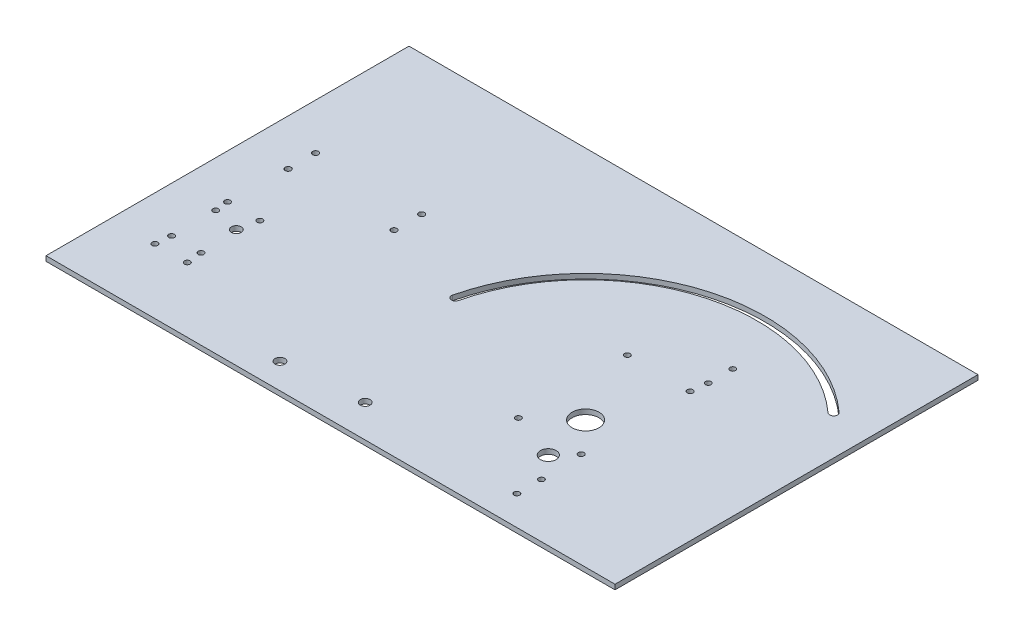
SolidWorks part; units mm, degrees
ref_plane "Front Plane" through (0, 0, 0) normal (0, 0, 1) x (1, 0, 0)
ref_plane "Top Plane" through (0, 0, 0) normal (0, 1, 0) x (1, 0, 0)
ref_plane "Right Plane" through (0, 0, 0) normal (1, 0, 0) x (0, 0, -1)
sketch "Sketch1" plane through (0, 0, 0) normal (0, 1, 0) x (1, 0, 0)
  line L1 (-158.75, 88.9) -> (158.75, 88.9)
  line L2 (-158.75, 88.9) -> (-158.75, -88.9)
  line L3 (-158.75, -88.9) -> (158.75, -88.9)
  line L4 (158.75, 88.9) -> (158.75, -88.9)
  line L5 (-158.75, 88.9) -> (158.75, -88.9) construction
  line L6 (-158.75, -88.9) -> (158.75, 88.9) construction
  circle A0 centre (-111.76, -12.7) radius 3.175
  circle A1 centre (107.95, -6.35) radius 8.7313
  circle A4 centre (-129.032, 55.88) radius 1.905
  circle A5 centre (-60.452, 55.88) radius 1.905
  circle A7 centre (-129.032, 38.1) radius 1.905
  circle A8 centre (-60.452, 38.1) radius 1.905
  point P0 (0, 0)
  dimension "D3" = 6.35
  dimension "D4" = 17.4625
  dimension "D14" = 3.81
  dimension "D17" = 17.78
  dimension "D1" = 317.5
  dimension "D2" = 177.8
  dimension "D5" = 46.99
  dimension "D6" = 266.7
  dimension "D7" = 95.25
  dimension "D8" = 76.2
  dimension "D13" = 29.718
  dimension "D15" = 68.58
  dimension "D16" = 127
extrude "Boss-Extrude1" add sketch "Sketch1" along normal blind 3.175
sketch "Sketch2" plane through (0, 3.175, 0) normal (0, 1, 0) x (1, 0, 0)
  line L0 (-158.75, 88.9) -> (-158.75, -88.9) construction
  line L1 (-158.75, -88.9) -> (158.75, -88.9) construction
  circle A0 centre (-89.0817, -33.177) radius 1.905
  circle A1 centre (-132.1376, -36.4483) radius 1.905
  dimension "D1" = 3.81
  dimension "D2" = 69.6683
  dimension "D3" = 52.4517
  dimension "D4" = 55.723
  dimension "D5" = 43.18
extrude "Cut-Extrude1" [suppressed] cut sketch "Sketch2" against normal through all
sketch "Sketch3" plane through (0, 0, 0) normal (0, -1, 0) x (-1, 0, 0)
  line L0 (158.75, -88.9) -> (-158.75, -88.9) construction
  line L1 (158.75, 88.9) -> (158.75, -88.9) construction
  circle A0 centre (23.8295, -72.39) radius 3.175
  circle A1 centre (-26.7643, -67.818) radius 3.175
  dimension "D1" = 6.35
  dimension "D2" = 4.572
  dimension "D3" = 16.51
  dimension "D4" = 185.5143
  dimension "D5" = 50.8
extrude "Cut-Extrude2" cut sketch "Sketch3" against normal through all
sketch "Sketch4" plane through (0, 3.175, 0) normal (0, 1, 0) x (1, 0, 0)
  line L0 (-158.75, -88.9) -> (158.75, -88.9) construction
  line L1 (158.75, 88.9) -> (133.35, 88.9)
  line L2 (158.75, 88.9) -> (158.75, -88.9)
  line L3 (158.75, -88.9) -> (133.35, -88.9)
  line L4 (133.35, 88.9) -> (133.35, -88.9)
  dimension "D1" = 25.4
extrude "Cut-Extrude3" cut sketch "Sketch4" against normal through all
sketch "Sketch5" plane through (0, 3.175, 0) normal (0, 1, 0) x (1, 0, 0)
  line L0 (133.35, 88.9) -> (-158.75, 88.9) construction
  line L1 (133.35, 88.9) -> (133.35, -88.9) construction
  circle A0 centre (115.57, -38.1) radius 5.08
  dimension "D3" = 10.16
  dimension "D1" = 127
  dimension "D2" = 17.78
extrude "Cut-Extrude4" cut sketch "Sketch5" against normal through all
sketch "Sketch6" plane through (0, 0, 0) normal (0, -1, 0) x (1, 0, 0)
  line L0 (-158.75, 88.9) -> (133.35, 88.9) construction
  line L1 (133.35, -88.9) -> (133.35, 88.9) construction
  line L2 (133.35, -88.9) -> (-158.75, -88.9) construction
  circle A0 centre (127, 69.85) radius 1.8034
  circle A2 centre (127, 53.975) radius 1.8034
  circle A3 centre (127, -53.975) radius 1.8034
  circle A4 centre (127, -69.85) radius 1.8034
  dimension "D4" = 3.6068
  dimension "D5" = 6.35
  dimension "D1" = 15.875
  dimension "D2" = 19.05
  dimension "D3" = 6.35
  dimension "D6" = 15.875
  dimension "D7" = 19.05
extrude "Cut-Extrude5" cut sketch "Sketch6" against normal through all
sketch "Sketch7" plane through (0, 3.175, 0) normal (0, 1, 0) x (1, 0, 0)
  line L0 (133.35, 88.9) -> (133.35, -88.9) construction
  line L1 (133.35, 88.9) -> (-158.75, 88.9) construction
  line L2 (-158.75, 88.9) -> (-158.75, -88.9) construction
  line L3 (-158.75, -88.9) -> (133.35, -88.9) construction
  circle A1 centre (125.73, 43.4975) radius 1.8415
  circle A2 centre (85.09, 43.4975) radius 1.8415
  circle A3 centre (85.09, -26.9875) radius 1.8415
  circle A4 centre (125.73, -26.9875) radius 1.8415
  circle A5 centre (-130.175, -46.99) radius 1.8415
  circle A6 centre (-109.22, -46.99) radius 1.8415
  circle A7 centre (-129.2225, -37.1475) radius 1.8415
  circle A8 centre (-110.1725, -37.1475) radius 1.8415
  circle A9 centre (-129.2225, -8.5725) radius 1.8415
  circle A10 centre (-130.175, 0) radius 1.8415
  circle A11 centre (-109.22, 0) radius 1.8415
  dimension "D1" = 7.62
  dimension "D5" = 3.683
  dimension "D10" = 3.683
  dimension "D15" = 3.683
  dimension "D2" = 40.64
  dimension "D3" = 70.485
  dimension "D4" = 61.9125
  dimension "D6" = 28.575
  dimension "D7" = 20.955
  dimension "D8" = 0.9525
  dimension "D9" = 19.05
  dimension "D11" = 88.9
  dimension "D12" = 8.5725
  dimension "D13" = 28.575
  dimension "D14" = 9.8425
extrude "Cut-Extrude6" cut sketch "Sketch7" against normal through all
sketch "Sketch8" plane through (0, 0, 0) normal (0, -1, 0) x (1, 0, 0)
  line L1 (-158.75, -88.9) -> (-158.75, 88.9) construction
  line L2 (-158.75, 88.9) -> (133.35, 88.9) construction
  line L3 (133.35, 88.9) -> (133.35, -88.9)
  line L4 (133.35, -88.9) -> (-158.75, -88.9) construction
  line L5 (133.35, -88.9) -> (-158.75, -88.9)
  line L6 (-158.75, -88.9) -> (-158.75, -146.05)
  line L7 (-158.75, -146.05) -> (209.55, -146.05)
  line L8 (209.55, -146.05) -> (209.55, 88.9)
  line L9 (209.55, 88.9) -> (133.35, 88.9)
  line L12 (133.35, -88.9) -> (133.35, 88.9) construction
  dimension "D1" = 76.2
  dimension "D2" = 57.15
extrude "Boss-Extrude2" add sketch "Sketch8" against normal through all
sketch "Sketch9" plane through (0, 0, 0) normal (0, -1, 0) x (1, 0, 0)
  line L0 (209.55, -146.05) -> (209.55, 88.9) construction
  arc A0 (185.8528, -79.875) -> (182.4472, -76.1056) centre (184.15, -77.9903) ccw
  arc A1 (-0.15, -19.402) -> (-5.0917, -20.5792) centre (-2.6208, -19.9906) ccw
  circle A2 centre (107.95, 6.35) radius 113.665 construction
  arc A3 (182.4472, -76.1056) -> (-0.15, -19.402) centre (107.95, 6.35) cw
  arc A4 (185.8528, -79.875) -> (-5.0917, -20.5792) centre (107.95, 6.35) cw
  arc A5 (-5.0917, -20.5792) -> (-2.0046, -22.4547) centre (-2.6208, -19.9906) ccw construction
  arc A6 (-2.0046, -22.4547) -> (-0.15, -19.402) centre (-2.6208, -19.9906) ccw construction
  arc A7 (182.2464, -79.672) -> (185.8528, -79.875) centre (184.15, -77.9903) ccw construction
  arc A8 (182.4472, -76.1056) -> (182.2464, -79.672) centre (184.15, -77.9903) ccw construction
  circle A9 centre (107.95, 6.35) radius 8.7313 construction
  point P1 (0, 0)
  dimension "D1" = 5.08
  dimension "D6" = 227.33
  dimension "D2" = 25.4
  dimension "D5" = 186.7708
extrude "Cut-Extrude7" cut sketch "Sketch9" against normal through all
